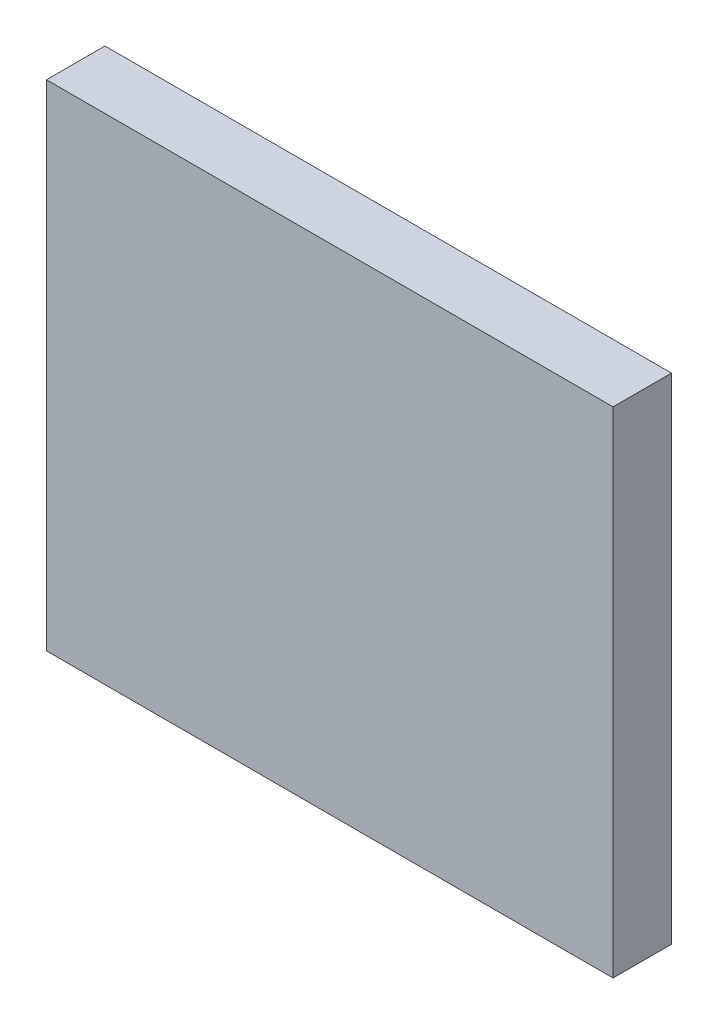
SolidWorks part; units mm, degrees
ref_plane "Front Plane" through (0, 0, 0) normal (0, 0, 1) x (1, 0, 0)
ref_plane "Top Plane" through (0, 0, 0) normal (0, 1, 0) x (1, 0, 0)
ref_plane "Right Plane" through (0, 0, 0) normal (1, 0, 0) x (0, 0, -1)
sketch "Sketch1" plane through (0, 0, 0) normal (0, 0, 1) x (1, 0, 0)
  line L1 (-31.5, 27.5) -> (31.5, 27.5)
  line L2 (-31.5, 27.5) -> (-31.5, -27.5)
  line L3 (-31.5, -27.5) -> (31.5, -27.5)
  line L4 (31.5, 27.5) -> (31.5, -27.5)
  line L5 (-31.5, 27.5) -> (31.5, -27.5) construction
  line L6 (-31.5, -27.5) -> (31.5, 27.5) construction
  point P0 (0, 0)
extrude "Boss-Extrude1" add sketch "Sketch1" along normal blind 6.5
